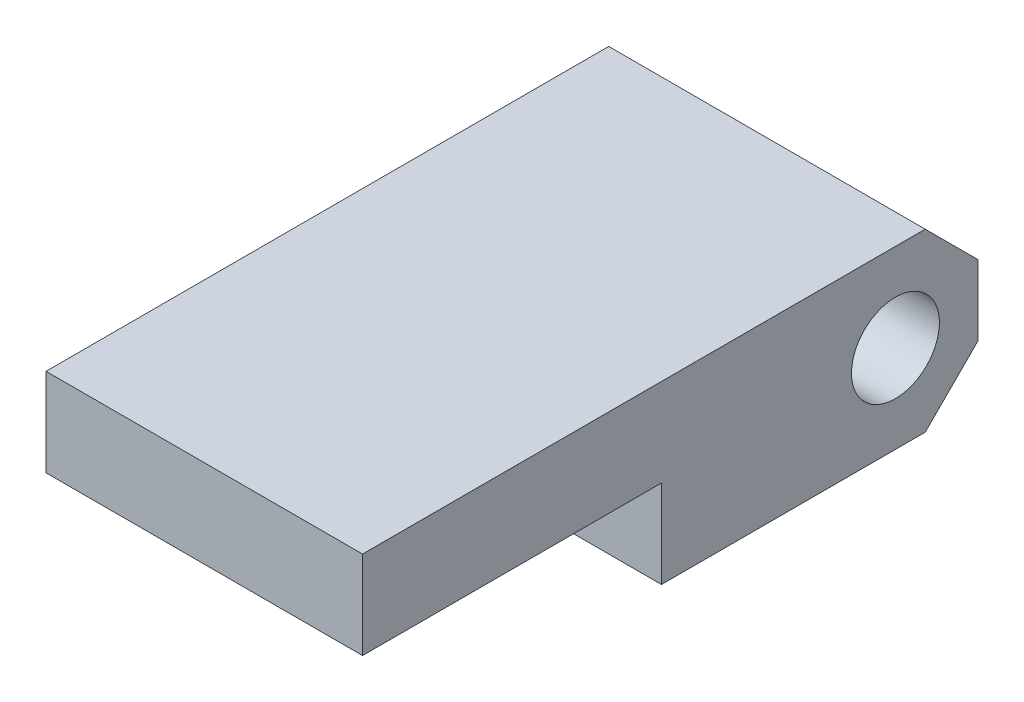
SolidWorks part; units mm, degrees
ref_plane "Спереди" through (0, 0, 0) normal (0, 0, 1) x (1, 0, 0)
ref_plane "Сверху" through (0, 0, 0) normal (0, 1, 0) x (1, 0, 0)
ref_plane "Справа" through (0, 0, 0) normal (1, 0, 0) x (0, 0, -1)
sketch "Эскиз1" plane through (0, 0, 0) normal (0, 1, 0) x (1, 0, 0)
  line L1 (0, 0) -> (18, 0)
  line L2 (0, 0) -> (0, -35)
  line L3 (0, -35) -> (18, -35)
  line L4 (18, 0) -> (18, -35)
extrude "Вытянуть1" add sketch "Эскиз1" along normal blind 10
sketch "Эскиз2" plane through (18, 0, 0) normal (1, 0, 0) x (0, 0, -1)
  line L0 (-35, 5) -> (-18, 5)
  line L1 (-35, 10) -> (-35, 0) construction
  line L2 (-18, 5) -> (-18, 0)
  line L3 (-35, 0) -> (0, 0) construction
  line L4 (-18, 0) -> (-35, 0)
  line L5 (-35, 0) -> (-35, 5)
  line L6 (-35, 5) -> (-34.9405, 5)
extrude "Вытянуть2" cut sketch "Эскиз2" against normal through all contours L0 L2 L4 L5
sketch "Эскиз3" plane through (0, 0, 0) normal (-1, 0, 0) x (0, 0, 1)
  circle A0 centre (4.6956, 5) radius 2.5
extrude "Вырез-Вытянуть1" cut sketch "Эскиз3" against normal through all
chamfer "Фаска1" distance 3 angle 45 2 edges at (9, 0, 0) (9, 10, 0)
